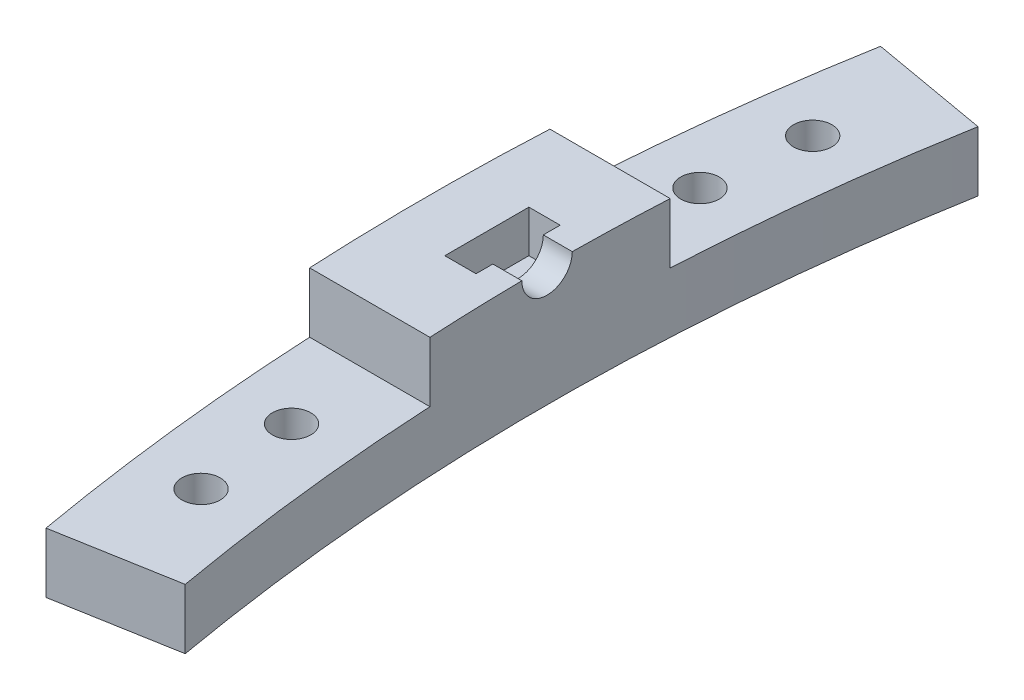
SolidWorks part; units mm, degrees
ref_plane "Front Plane" through (0, 0, 0) normal (0, 0, 1) x (1, 0, 0)
ref_plane "Top Plane" through (0, 0, 0) normal (0, 1, 0) x (1, 0, 0)
ref_plane "Right Plane" through (0, 0, 0) normal (1, 0, 0) x (0, 0, -1)
sketch "Sketch1" plane through (0, 0, 0) normal (0, 1, 0) x (1, 0, 0)
  line L0 (0, 0) -> (-196.9616, -34.7296) construction
  line L1 (0, 0) -> (-196.9616, 34.7296) construction
  line L2 (0, 0) -> (-195, 0) construction
  line L3 (-196.9616, 34.7296) -> (-187.1135, 32.9932)
  line L4 (-187.1135, -32.9932) -> (-196.9616, -34.7296)
  arc A0 (-196.9616, 34.7296) -> (-196.9616, -34.7296) centre (0, 0) ccw
  arc A1 (-187.1135, 32.9932) -> (-187.1135, -32.9932) centre (0, 0) ccw
  arc A2 (-192.0375, -33.8614) -> (-192.0375, 33.8614) centre (0, 0) cw construction
  dimension "D1" = 200
  dimension "D2" = 190
  dimension "D3" = 5
  dimension "D4" = 20
extrude "Boss-Extrude1" add sketch "Sketch1" along normal blind 5
sketch "Sketch2" [suppressed] plane through (0, 7.5, 0) normal (0, 1, 0) x (1, 0, 0)
  line L2 (0, 0) -> (-195, 0) construction
  line L3 (0, 0) -> (-199.4236, -35.1638) construction
  line L4 (0, 0) -> (-199.4236, 35.1638) construction
  line L5 (0, 0) -> (-190, 0) construction
  line L6 (0, 0) -> (-199.4236, -35.1638) construction
  line L7 (0, 0) -> (-199.4236, 35.1638) construction
  line L8 (0, 10) -> (-202.2529, 10) construction
  line L9 (0, 10) -> (0, -10) construction
  line L10 (0, -10) -> (-202.2529, -10) construction
  line L11 (-196.9616, 34.7296) -> (-187.1135, 32.9932)
  line L12 (-196.9616, -34.7296) -> (-187.1135, -32.9932)
  line L13 (-199.7498, -10) -> (-189.7367, -10)
  line L14 (-189.7367, 10) -> (-199.7498, 10)
  arc A0 (-196.9616, 34.7296) -> (-196.9616, -34.7296) centre (0, 0) ccw construction
  arc A1 (-187.1135, 32.9932) -> (-187.1135, -32.9932) centre (0, 0) ccw construction
  arc A2 (-196.9616, 34.7296) -> (-196.9616, -34.7296) centre (0, 0) ccw
  arc A3 (-187.1135, 32.9932) -> (-187.1135, -32.9932) centre (0, 0) ccw
  arc A4 (-199.4236, 35.1638) -> (-199.4236, -35.1638) centre (0, 0) ccw construction
  line M2 (-199.4236, -35.1638) -> (-184.6515, -32.559)
  line M4 (-184.6515, 32.559) -> (-199.4236, 35.1638)
  dimension "D1" = 20
extrude "Cut-Extrude1" [suppressed] cut sketch "Sketch2" against normal blind 1.5 contours A3 A2 L14 M4 | A3 L13 A2 M2
ref_plane "Plane1" through (-195, 0, 0) normal (1, 0, 0) x (0, 0, -1)
sketch "Sketch6" [suppressed] plane through (0, 0, 0) normal (0, -1, 0) x (1, 0, 0)
  line L0 (0, 0) -> (-194.258, 16.9954) construction
  line L1 (0, 0) -> (-195, 0) construction
  line L2 (0, 0) -> (-195, 0) construction
  line L3 (0, 0) -> (-194.258, -16.9954) construction
  arc A0 (-192.0375, 33.8614) -> (-192.0375, -33.8614) centre (0, 0) ccw construction
  dimension "D1" = 5
hole_wizard "Ø3.1 (3.1) Diameter Hole1" [suppressed] positions "Sketch7" profile "Sketch8" hole size "Ø3.1" standard "ISO"
sketch "Sketch7" [suppressed] plane through (0, 0, 0) normal (0, -1, 0) x (-1, 0, 0)
  point P0 (194.258, -16.9954)
  point P3 (194.258, 16.9954)
sketch "Sketch8" plane through (-194.258, 0, 16.9954) normal (1, 0, 0) x (0, 0, -1)
  line L0 (0, 0) -> (0, 7.5)
  line L1 (0, 7.5) -> (1.55, 7.5)
  line L2 (1.55, 7.5) -> (1.55, 0)
  line L5 (1.55, 0) -> (0, 0)
  line L11 (0, -6.35) -> (0, 107.95) construction
  dimension "Thru Hole Dia." = 3.1
  dimension "Thru Hole Depth" = 7.5
sketch "Sketch9" plane through (0, 5, 0) normal (0, 1, 0) x (1, 0, 0)
  line L0 (0, 10) -> (0, -10) construction
  line L1 (0, 0) -> (-200, 0) construction
  line L2 (-199.7498, 10) -> (-189.7367, 10)
  line L3 (-199.7498, -10) -> (-189.7367, -10)
  arc A0 (-196.9616, 34.7296) -> (-196.9616, -34.7296) centre (0, 0) ccw construction
  arc A1 (-187.1135, 32.9932) -> (-187.1135, -32.9932) centre (0, 0) ccw construction
  arc A2 (-189.7367, 10) -> (-189.7367, -10) centre (0, 0) ccw
  arc A3 (-199.7498, 10) -> (-199.7498, -10) centre (0, 0) ccw
  dimension "D1" = 20
extrude "Boss-Extrude2" add sketch "Sketch9" along normal blind 5
ref_plane "Plane2" through (-195, 0, 0) normal (-1, 0, 0) x (0, 0, 1)
sketch "Sketch10" plane through (-195, 0, 0) normal (-1, 0, 0) x (0, 0, 1)
  line L0 (10, 10) -> (-10, 10) construction
  line L1 (3.5, 13.5) -> (-3.5, 13.5)
  line L2 (3.5, 13.5) -> (3.5, 6.5)
  line L3 (3.5, 6.5) -> (-3.5, 6.5)
  line L4 (-3.5, 13.5) -> (-3.5, 6.5)
  line L5 (3.5, 13.5) -> (-3.5, 6.5) construction
  line L6 (3.5, 6.5) -> (-3.5, 13.5) construction
  point P0 (0, 10)
  dimension "D1" = 7
  dimension "D2" = 7
extrude "Cut-Extrude2" cut sketch "Sketch10" against normal blind 2.6
sketch "Sketch11" plane through (-195, 0, 0) normal (-1, 0, 0) x (0, 0, 1)
  line L0 (10, 10) -> (-10, 10) construction
  circle A0 centre (0, 10) radius 2.1
  dimension "D1" = 4.2
extrude "Cut-Extrude3" cut sketch "Sketch11" against normal through all
sketch "Sketch12" plane through (0, 5, 0) normal (0, 1, 0) x (1, 0, 0)
  line L0 (0, 0) -> (-194.258, -16.9954) construction
  line L1 (0, 0) -> (-193.3317, -25.4526) construction
  line L2 (0, 0) -> (-195, 0) construction
  line L3 (0, 0) -> (-195, 0) construction
  line L4 (0, 0) -> (-194.258, 16.9954) construction
  line L5 (0, 0) -> (-193.3317, 25.4526) construction
  arc A0 (-192.0375, 33.8614) -> (-192.0375, -33.8614) centre (0, 0) ccw construction
  dimension "D1" = 10
  dimension "D2" = 15
hole_wizard "Ø3.2 (3.2) Diameter Hole1" positions "Sketch13" profile "Sketch14" hole size "Ø3.2" standard "ISO" end condition through all
sketch "Sketch13" plane through (0, 5, 0) normal (0, 1, 0) x (1, 0, 0)
  point P0 (-194.258, 16.9954)
  point P3 (-193.3317, 25.4526)
  point P6 (-194.258, -16.9954)
  point P9 (-193.3317, -25.4526)
sketch "Sketch14" plane through (-194.258, 5, -16.9954) normal (1, 0, 0) x (0, 0, 1)
  line L0 (0, 0) -> (0, 5)
  line L1 (0, 5) -> (1.6, 5)
  line L2 (1.6, 5) -> (1.6, 0)
  line L5 (1.6, 0) -> (0, 0)
  line L11 (0, -6.35) -> (0, 107.95) construction
  dimension "Thru Hole Dia." = 3.2
  dimension "Thru Hole Depth" = 5
